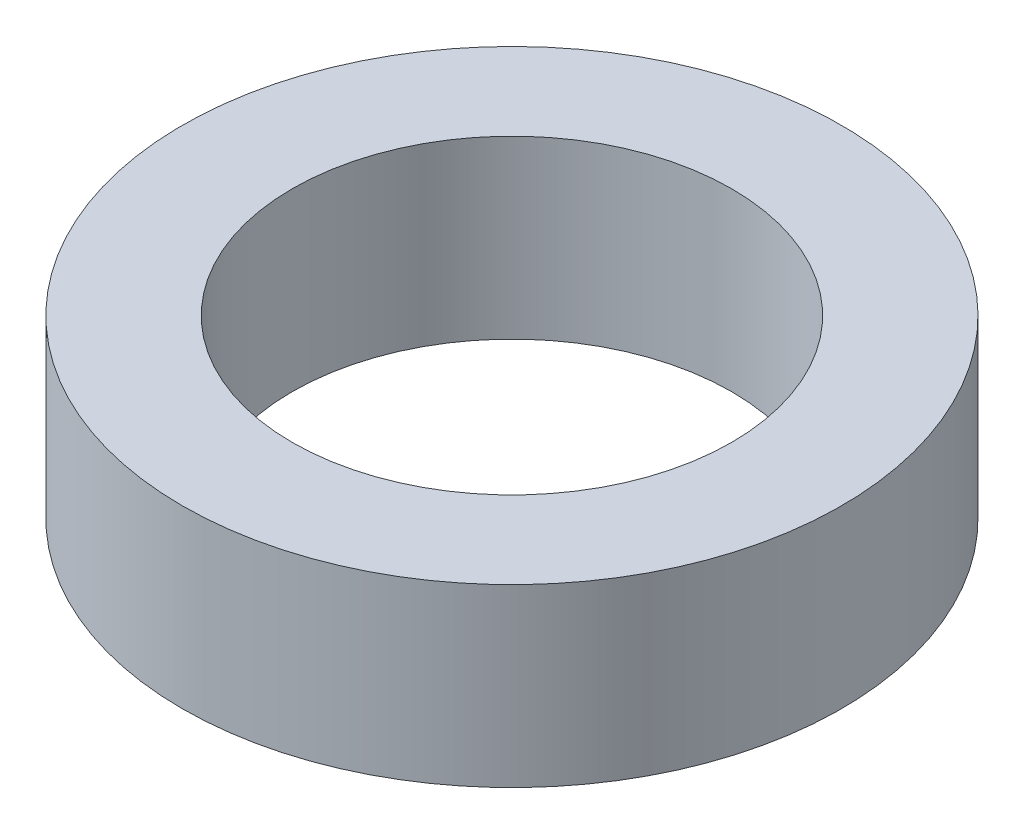
SolidWorks part; units mm, degrees
material "1060 合金"
ref_plane "前视基准面" through (0, 0, 0) normal (0, 0, 1) x (1, 0, 0)
ref_plane "上视基准面" through (0, 0, 0) normal (0, 1, 0) x (1, 0, 0)
ref_plane "右视基准面" through (0, 0, 0) normal (1, 0, 0) x (0, 0, -1)
other "Configuration Table"
sketch "草图1" plane through (0, 0, 0) normal (0, 1, 0) x (1, 0, 0)
  circle A0 centre (0, 0) radius 5
  circle A1 centre (0, 0) radius 7.5
  dimension "D1" = 10
  dimension "D2" = 15
extrude "凸台-拉伸1" add sketch "草图1" along normal blind 4
